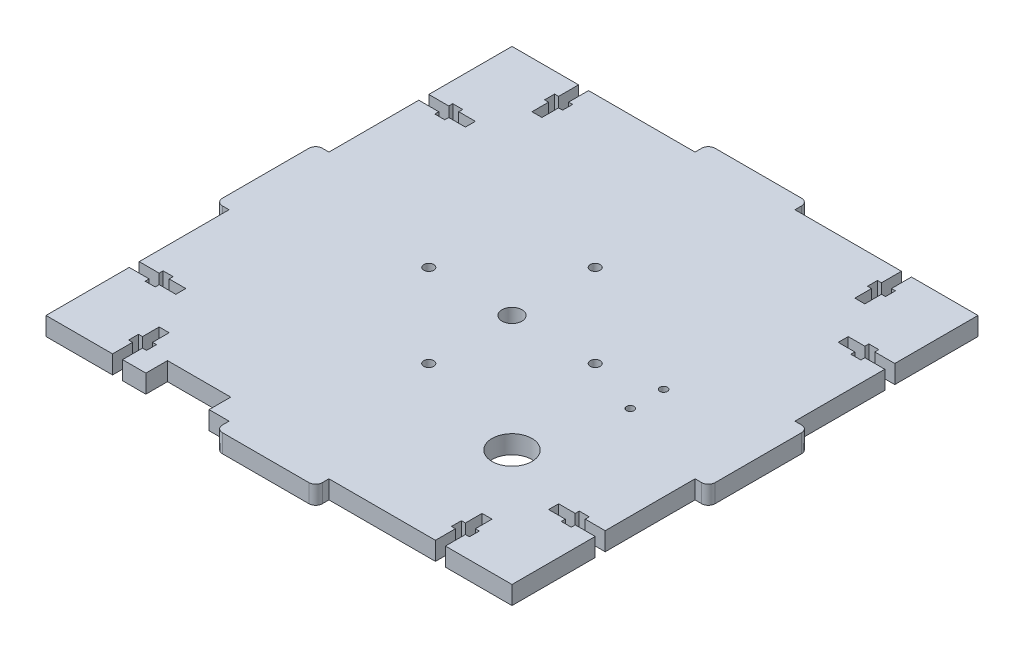
SolidWorks part; units mm, degrees
ref_plane "Front Plane" through (0, 0, 0) normal (0, 0, 1) x (1, 0, 0)
ref_plane "Top Plane" through (0, 0, 0) normal (0, 1, 0) x (1, 0, 0)
ref_plane "Right Plane" through (0, 0, 0) normal (1, 0, 0) x (0, 0, -1)
sketch "Sketch1" plane through (0, 0, 0) normal (0, 1, 0) x (1, 0, 0)
  line L0 (85, 0) -> (117, 0)
  line L1 (0, 0) -> (20, 0)
  line L2 (0, 0) -> (0, 25)
  line L3 (0, 140) -> (20, 140)
  line L4 (140, 0) -> (140, 25)
  line L5 (20, 9) -> (20, 14)
  line L6 (55, 0) -> (55, -4)
  line L7 (55, -4) -> (85, -4)
  line L8 (85, 0) -> (85, -4)
  line L9 (120, 0) -> (140, 0)
  line L10 (20, 0) -> (20, 6)
  line L11 (20, 14) -> (23, 14)
  line L12 (23, 0) -> (23, 6)
  line L13 (23, 9) -> (24.2, 9)
  line L14 (23, 0) -> (30, 0)
  line L15 (23, 6) -> (24.2, 6)
  line L16 (24.2, 9) -> (24.2, 6)
  line L17 (20, 9) -> (18.8, 9)
  line L18 (120, 9) -> (120, 14)
  line L19 (20, 6) -> (18.8, 6)
  line L20 (18.8, 9) -> (18.8, 6)
  line L21 (23, 9) -> (23, 14)
  line L22 (117, 9) -> (117, 14)
  line L23 (120, 0) -> (120, 6)
  line L24 (120, 14) -> (117, 14)
  line L25 (117, 0) -> (117, 6)
  line L26 (120, 9) -> (121.2, 9)
  line L27 (0, 28) -> (0, 55)
  line L28 (120, 6) -> (121.2, 6)
  line L29 (121.2, 9) -> (121.2, 6)
  line L30 (117, 9) -> (115.8, 9)
  line L31 (0, 28) -> (6, 28)
  line L32 (117, 6) -> (115.8, 6)
  line L33 (115.8, 9) -> (115.8, 6)
  line L34 (9, 28) -> (14, 28)
  line L35 (0, 25) -> (6, 25)
  line L36 (14, 28) -> (14, 25)
  line L37 (140, 28) -> (140, 55)
  line L38 (6, 25) -> (6, 23.8)
  line L39 (6, 23.8) -> (9, 23.8)
  line L40 (9, 25) -> (9, 23.8)
  line L41 (131, 28) -> (126, 28)
  line L42 (6, 28) -> (6, 29.2)
  line L43 (6, 29.2) -> (9, 29.2)
  line L44 (9, 28) -> (9, 29.2)
  line L45 (9, 25) -> (14, 25)
  line L46 (140, 28) -> (134, 28)
  line L47 (131, 25) -> (126, 25)
  line L48 (140, 25) -> (134, 25)
  line L49 (126, 28) -> (126, 25)
  line L50 (140, 85) -> (140, 112)
  line L51 (134, 25) -> (134, 23.8)
  line L52 (134, 23.8) -> (131, 23.8)
  line L53 (131, 25) -> (131, 23.8)
  line L54 (140, 85) -> (144, 85)
  line L55 (134, 28) -> (134, 29.2)
  line L56 (134, 29.2) -> (131, 29.2)
  line L57 (131, 28) -> (131, 29.2)
  line L58 (85, 140) -> (117, 140)
  line L59 (140, 55) -> (144, 55)
  line L60 (144, 85) -> (144, 55)
  line L61 (0, 85) -> (0, 112)
  line L62 (55, 140) -> (55, 144)
  line L63 (55, 144) -> (85, 144)
  line L64 (85, 140) -> (85, 144)
  line L65 (0, 85) -> (-4, 85)
  line L66 (0, 115) -> (0, 140)
  line L67 (0, 55) -> (-4, 55)
  line L68 (-4, 85) -> (-4, 55)
  line L69 (0, 115) -> (6, 115)
  line L70 (23, 140) -> (55, 140)
  line L71 (0, 112) -> (6, 112)
  line L72 (14, 115) -> (14, 112)
  line L73 (140, 115) -> (140, 140)
  line L74 (20, 140) -> (20, 134)
  line L75 (20, 126) -> (23, 126)
  line L76 (23, 140) -> (23, 134)
  line L77 (20, 131) -> (20, 126)
  line L78 (120, 140) -> (120, 134)
  line L79 (120, 126) -> (117, 126)
  line L80 (117, 140) -> (117, 134)
  line L81 (140, 115) -> (134, 115)
  line L82 (120, 140) -> (140, 140)
  line L83 (140, 112) -> (134, 112)
  line L84 (126, 115) -> (126, 112)
  line L85 (18.8, 134) -> (20, 134)
  line L86 (18.8, 134) -> (18.8, 131)
  line L87 (18.8, 131) -> (20, 131)
  line L88 (24.2, 134) -> (24.2, 131)
  line L89 (23, 131) -> (23, 126)
  line L90 (23, 134) -> (24.2, 134)
  line L91 (23, 131) -> (24.2, 131)
  line L92 (6, 112) -> (6, 110.8)
  line L93 (6, 116.2) -> (9, 116.2)
  line L94 (6, 116.2) -> (6, 115)
  line L95 (6, 110.8) -> (9, 110.8)
  line L96 (9, 116.2) -> (9, 115)
  line L97 (9, 115) -> (14, 115)
  line L98 (9, 112) -> (9, 110.8)
  line L99 (9, 112) -> (14, 112)
  line L100 (120, 134) -> (121.2, 134)
  line L101 (115.8, 134) -> (117, 134)
  line L102 (115.8, 134) -> (115.8, 131)
  line L103 (115.8, 131) -> (117, 131)
  line L104 (121.2, 134) -> (121.2, 131)
  line L105 (131, 116.2) -> (134, 116.2)
  line L106 (131, 116.2) -> (131, 115)
  line L107 (131, 110.8) -> (134, 110.8)
  line L108 (134, 116.2) -> (134, 115)
  line L109 (117, 131) -> (117, 126)
  line L110 (120, 131) -> (120, 126)
  line L111 (120, 131) -> (121.2, 131)
  line L112 (134, 112) -> (134, 110.8)
  line L113 (131, 115) -> (126, 115)
  line L114 (131, 112) -> (126, 112)
  line L115 (131, 112) -> (131, 110.8)
  line L116 (49, 0) -> (55, 0)
  line L118 (30, 0) -> (30, 6.5)
  line L119 (30, 6.5) -> (49, 6.5)
  line L120 (49, 0) -> (49, 6.5)
  circle A0 centre (70, 70) radius 3
  circle A1 centre (70, 95) radius 1.5
  circle A2 centre (95, 70) radius 1.5
  circle A3 centre (70, 45) radius 1.5
  circle A4 centre (45, 70) radius 1.5
  circle A5 centre (105, 35) radius 6
  circle A6 centre (112, 73.5565) radius 1.125
  circle A7 centre (112, 63.5565) radius 1.125
  dimension "D3" = 6
  dimension "D86" = 3
  dimension "D87" = 3
  dimension "D88" = 3
  dimension "D89" = 3
  dimension "D90" = 12
  dimension "D97" = 2.25
  dimension "D98" = 2.25
  dimension "D1" = 140
  dimension "D2" = 140
  dimension "D4" = 70
  dimension "D5" = 70
  dimension "D6" = 30
  dimension "D7" = 4
  dimension "D8" = 20
  dimension "D9" = 3
  dimension "D10" = 14
  dimension "D11" = 6
  dimension "D12" = 6
  dimension "D13" = 3
  dimension "D14" = 3
  dimension "D15" = 1.2
  dimension "D16" = 1.2
  dimension "D17" = 20
  dimension "D18" = 3
  dimension "D19" = 14
  dimension "D20" = 1.2
  dimension "D21" = 1.2
  dimension "D22" = 6
  dimension "D23" = 6
  dimension "D24" = 3
  dimension "D25" = 3
  dimension "D26" = 25
  dimension "D27" = 14
  dimension "D28" = 3
  dimension "D29" = 6
  dimension "D30" = 6
  dimension "D31" = 3
  dimension "D32" = 3
  dimension "D33" = 1.2
  dimension "D34" = 1.2
  dimension "D35" = 55
  dimension "D36" = 14
  dimension "D37" = 3
  dimension "D38" = 25
  dimension "D39" = 3
  dimension "D40" = 6
  dimension "D41" = 6
  dimension "D42" = 3
  dimension "D43" = 1.2
  dimension "D44" = 1.2
  dimension "D45" = 55
  dimension "D46" = 30
  dimension "D47" = 4
  dimension "D48" = 55
  dimension "D49" = 30
  dimension "D50" = 4
  dimension "D51" = 4
  dimension "D52" = 55
  dimension "D53" = 30
  dimension "D54" = 14
  dimension "D55" = 3
  dimension "D56" = 25
  dimension "D57" = 20
  dimension "D58" = 3
  dimension "D59" = 20
  dimension "D60" = 3
  dimension "D61" = 14
  dimension "D62" = 14
  dimension "D63" = 25
  dimension "D64" = 3
  dimension "D65" = 14
  dimension "D66" = 6
  dimension "D67" = 1.2
  dimension "D68" = 5.4
  dimension "D69" = 3
  dimension "D70" = 5.4
  dimension "D71" = 1.2
  dimension "D72" = 3
  dimension "D73" = 6
  dimension "D74" = 1.2
  dimension "D75" = 5.4
  dimension "D76" = 3
  dimension "D77" = 6
  dimension "D78" = 6
  dimension "D79" = 3
  dimension "D80" = 1.2
  dimension "D81" = 5.4
  dimension "D82" = 25
  dimension "D83" = 25
  dimension "D84" = 25
  dimension "D85" = 25
  dimension "D91" = 35
  dimension "D92" = 35
  dimension "D93" = 7
  dimension "D94" = 19
  dimension "D95" = 6.5
  dimension "D96" = 10
  dimension "D99" = 17
  dimension "D100" = 17
extrude "Boss-Extrude1" add sketch "Sketch1" along normal blind 5.5
fillet "Fillet1" radius 2 8 edges at (-4, 2.75, -55) (-4, 2.75, -85) (55, 2.75, -144) (85, 2.75, -144) (144, 2.75, -85) (144, 2.75, -55) (85, 2.75, 4) (55, 2.75, 4)
